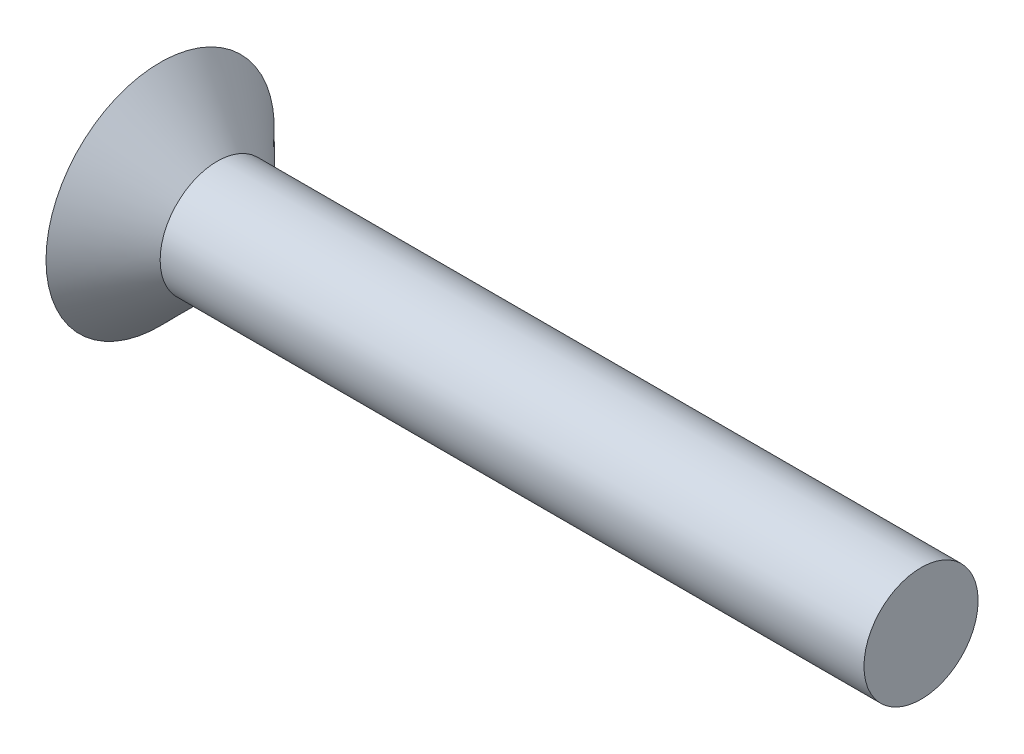
SolidWorks part; units mm, degrees
material "AISI 304"
ref_plane "前视基准面" through (0, 0, 0) normal (0, 0, 1) x (1, 0, 0)
ref_plane "上视基准面" through (0, 0, 0) normal (0, 1, 0) x (1, 0, 0)
ref_plane "右视基准面" through (0, 0, 0) normal (1, 0, 0) x (0, 0, -1)
sketch "草图1" plane through (0, 0, 0) normal (0, 0, 1) x (1, 0, 0)
  line L0 (0, 0) -> (0, 3)
  line L5 (0, 0) -> (20, 0) construction
  line L6 (20, 0) -> (20, 1.5)
  line L7 (20, 1.5) -> (1.5, 1.5)
  line L8 (1.5, 1.5) -> (0, 3)
  dimension "D1" = 3
  dimension "D2" = 20
  dimension "D3" = 6
  dimension "D5" = 45
revolve "旋转1" add sketch "草图1" angle 360 about L5
cosmetic thread "装饰螺纹线2" parameters "D2"=2.459
sketch "草图2" plane through (0, 0, 0) normal (-1, 0, 0) x (0, 0, 1)
  line L1 (0, 1.1547) -> (-1, 0.5774)
  line L2 (-1, 0.5774) -> (-1, -0.5774)
  line L3 (-1, -0.5774) -> (0, -1.1547)
  line L4 (0, -1.1547) -> (1, -0.5774)
  line L5 (1, -0.5774) -> (1, 0.5774)
  line L6 (1, 0.5774) -> (0, 1.1547)
  circle A0 centre (0, 0) radius 1 construction
  dimension "D1" = 1
extrude "切除-拉伸1" cut sketch "草图2" against normal blind 1
